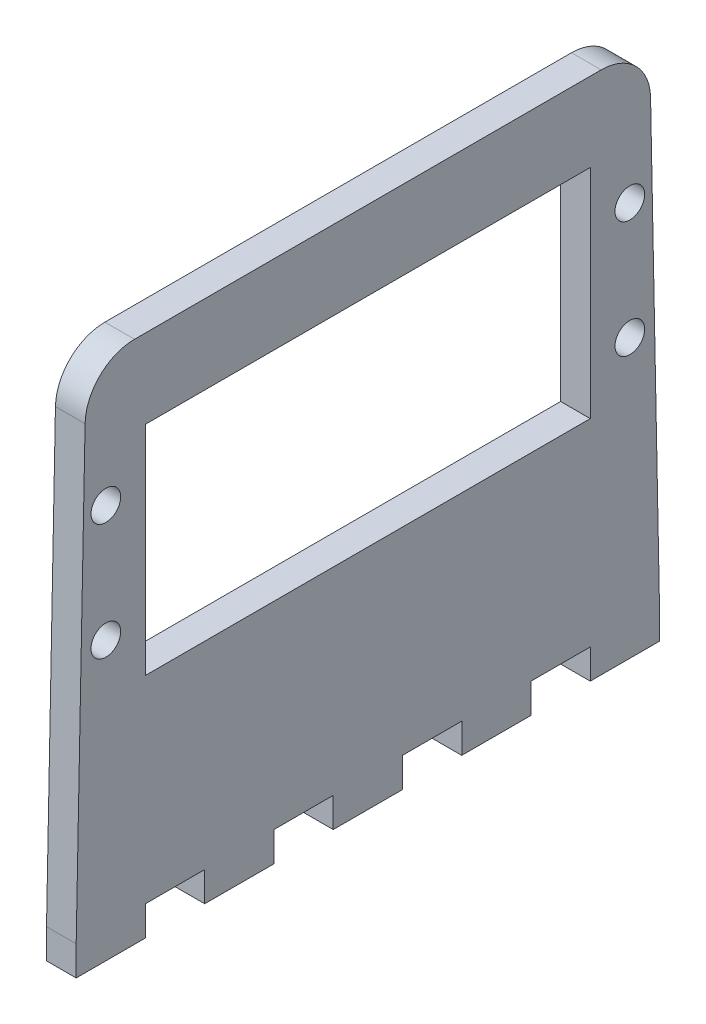
SolidWorks part; units mm, degrees
ref_plane "Front Plane" through (0, 0, 0) normal (0, 0, 1) x (1, 0, 0)
ref_plane "Top Plane" through (0, 0, 0) normal (0, 1, 0) x (1, 0, 0)
ref_plane "Right Plane" through (0, 0, 0) normal (1, 0, 0) x (0, 0, -1)
sketch "Sketch1" plane through (0, 0, 0) normal (1, 0, 0) x (0, 0, -1)
  line L0 (-33, 0) -> (-32, 50)
  line L1 (-32, 50) -> (25, 50)
  line L2 (25, 50) -> (26, 0)
  line L3 (26, 0) -> (26, -3)
  line L4 (26, -3) -> (19, -3)
  line L5 (19, -3) -> (19, 0)
  line L6 (19, 0) -> (13, 0)
  line L7 (13, 0) -> (13, -3)
  line L8 (13, -3) -> (6, -3)
  line L9 (6, -3) -> (6, 0)
  line L10 (6, 0) -> (0, 0)
  line L11 (0, 0) -> (0, -3)
  line L12 (0, -3) -> (-7, -3)
  line L13 (-7, -3) -> (-7, 0)
  line L14 (-7, 0) -> (-13, 0)
  line L15 (-13, 0) -> (-13, -3)
  line L16 (-13, -3) -> (-20, -3)
  line L17 (-20, -3) -> (-20, 0)
  line L18 (-20, 0) -> (-26, 0)
  line L19 (-26, 0) -> (-26, -3)
  line L20 (-26, -3) -> (-33, -3)
  line L21 (-33, -3) -> (-33, 0)
  line L22 (-3.5, 31) -> (-3.5, 36.1865) construction
  line L23 (-26, 42) -> (19, 42)
  line L24 (-26, 42) -> (-26, 20)
  line L25 (-26, 20) -> (19, 20)
  line L26 (19, 42) -> (19, 20)
  line L27 (-26, 42) -> (19, 20) construction
  line L28 (-26, 20) -> (19, 42) construction
  line L29 (-3.5, 31) -> (1.6461, 31) construction
  circle A0 centre (23, 36.9) radius 1.5
  circle A1 centre (23, 25.1) radius 1.5
  circle A2 centre (-30, 36.9) radius 1.5
  circle A3 centre (-30, 25.1) radius 1.5
  point P23 (-3.5, 31)
  point P38 (-3.5, -3)
  dimension "D7" = 20
  dimension "D8" = 3
  dimension "D1" = 7
  dimension "D2" = 3
  dimension "D3" = 6
  dimension "D4" = 22
  dimension "D5" = 45
  dimension "D6" = 8
  dimension "D9" = 5.1
  dimension "D10" = 4
  dimension "D12" = 57
extrude "Boss-Extrude1" add sketch "Sketch1" along normal blind 3
fillet "Fillet1" radius 5 2 edges at (1.5, 50, 32) (1.5, 50, -25)
